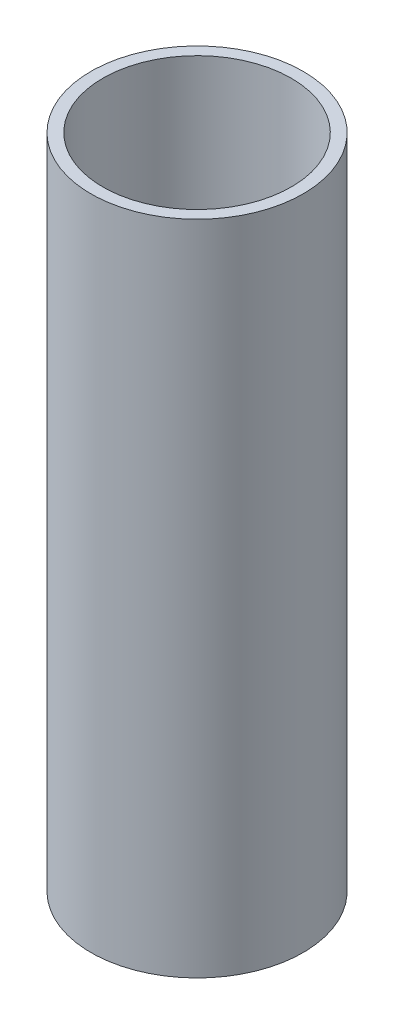
SolidWorks part; units mm, degrees
material "AISI 1020"
ref_plane "Front Plane" through (0, 0, 0) normal (0, 0, 1) x (1, 0, 0)
ref_plane "Top Plane" through (0, 0, 0) normal (0, 1, 0) x (1, 0, 0)
ref_plane "Right Plane" through (0, 0, 0) normal (1, 0, 0) x (0, 0, -1)
sketch "Sketch1" plane through (0, 0, 0) normal (0, 1, 0) x (1, 0, 0)
  circle A0 centre (13.6327, 6.0794) radius 7.0485
  circle A1 centre (13.6327, 6.0794) radius 7.9375
  dimension "D1" = 14.097
  dimension "D2" = 15.875
extrude "Boss-Extrude1" add sketch "Sketch1" along normal blind 49.14
